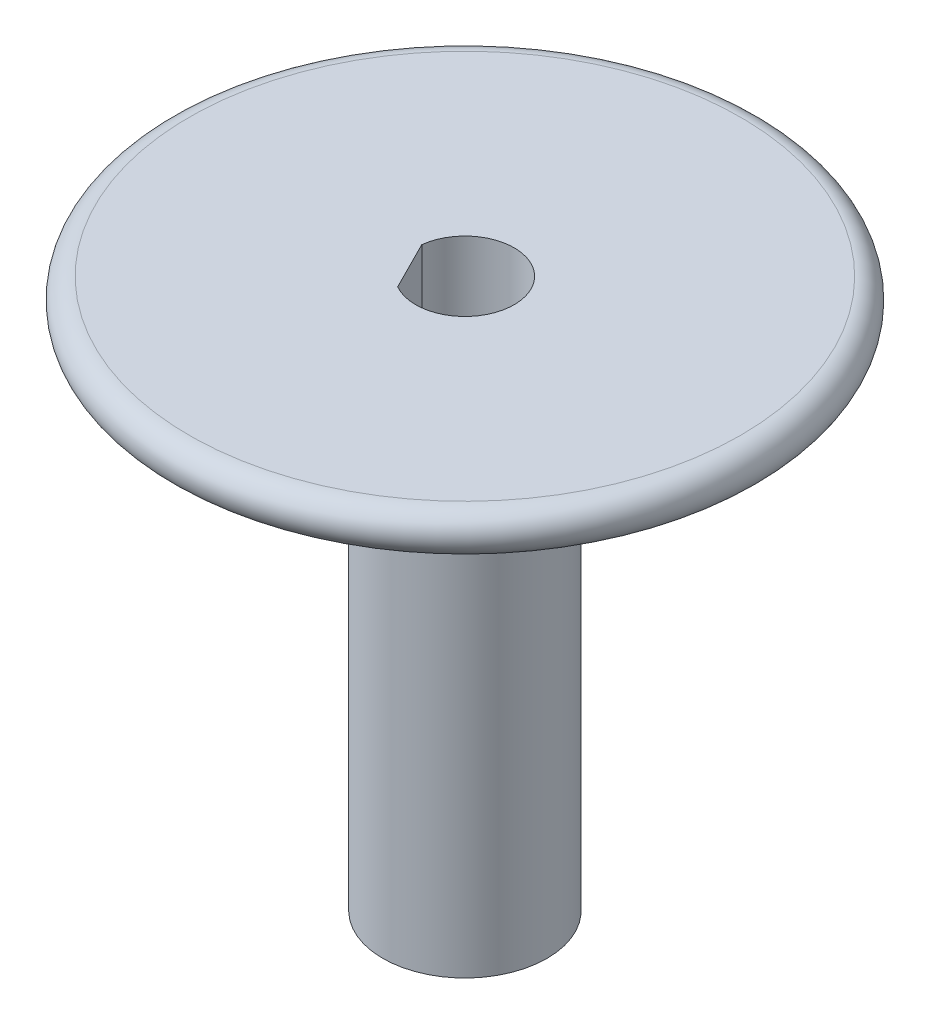
SolidWorks part; units mm, degrees
ref_plane "Front Plane" through (0, 0, 0) normal (0, 0, 1) x (1, 0, 0)
ref_plane "Top Plane" through (0, 0, 0) normal (0, 1, 0) x (1, 0, 0)
ref_plane "Right Plane" through (0, 0, 0) normal (1, 0, 0) x (0, 0, -1)
sketch "Sketch1" plane through (0, 0, 0) normal (0, 0, 1) x (1, 0, 0)
  line L0 (0, -15.7234) -> (0, 18.2634)
  line L1 (0, 18.2634) -> (17.0415, 18.2634)
  line L2 (5.08, 15.7234) -> (17.0415, 15.7234)
  line L5 (5.08, 15.7234) -> (5.08, -15.7234)
  line L6 (5.08, -15.7234) -> (0, -15.7234)
  arc A0 (17.0415, 18.2634) -> (17.0415, 15.7234) centre (17.0415, 16.9934) cw
  point P4 (0, 0)
  dimension "D1" = 2.54
  dimension "D3" = 5.08
revolve "Revolve1" add sketch "Sketch1" angle 360 about L0
sketch "Sketch2" plane through (0, 18.2634, 0) normal (0, 1, 0) x (1, 0, 0)
  line L0 (-1.5118, -2.6467) -> (-3.0268, 0.3585)
  arc A0 (-1.5118, -2.6467) -> (-3.0268, 0.3585) centre (0, 0) ccw
  dimension "D1" = 3.3655
extrude "Cut-Extrude1" cut sketch "Sketch2" against normal through all
